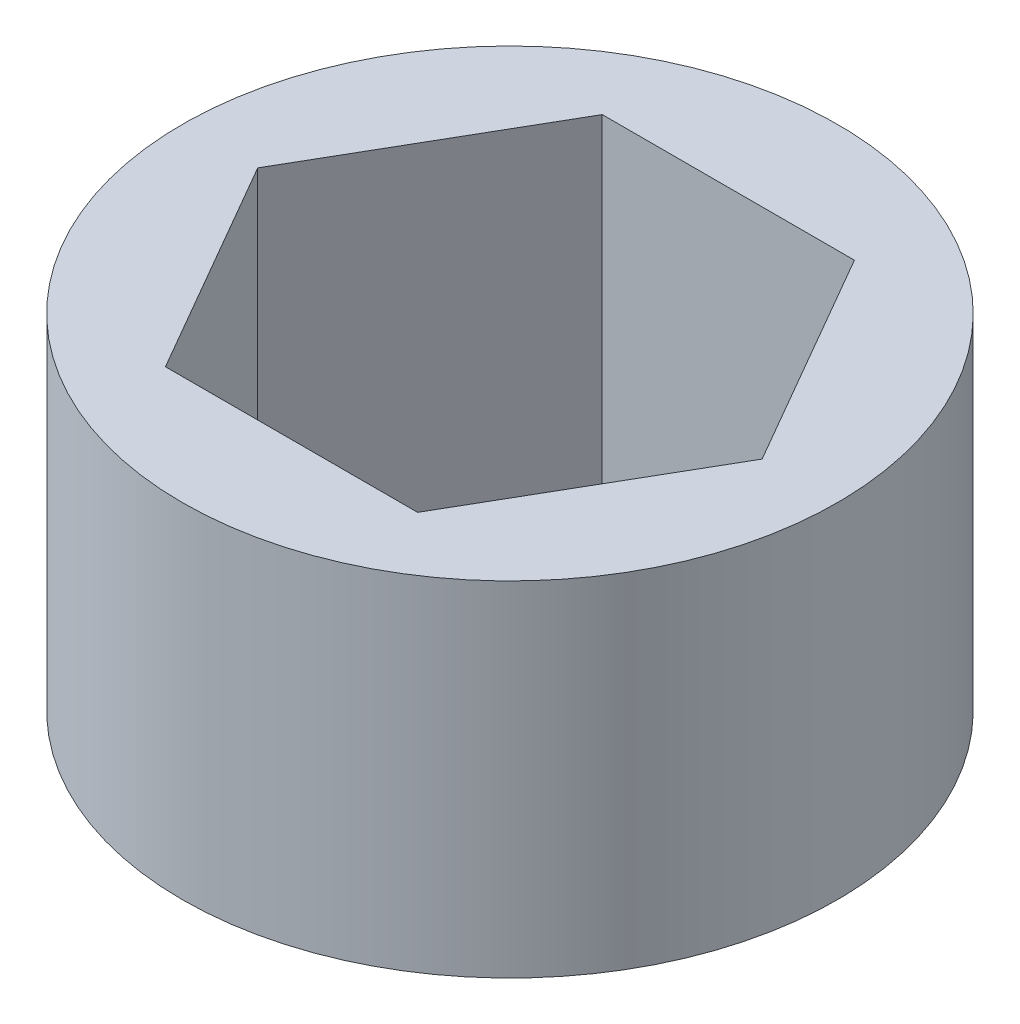
SolidWorks part; units mm, degrees
ref_plane "Alzado" through (0, 0, 0) normal (0, 0, 1) x (1, 0, 0)
ref_plane "Planta" through (0, 0, 0) normal (0, 1, 0) x (1, 0, 0)
ref_plane "Vista lateral" through (0, 0, 0) normal (1, 0, 0) x (0, 0, -1)
sketch "Croquis1" plane through (0, 0, 0) normal (0, 1, 0) x (1, 0, 0)
  line L1 (7.3323, 0) -> (3.6662, 6.35)
  line L2 (3.6662, 6.35) -> (-3.6662, 6.35)
  line L3 (-3.6662, 6.35) -> (-7.3323, 0)
  line L4 (-7.3323, 0) -> (-3.6662, -6.35)
  line L5 (-3.6662, -6.35) -> (3.6662, -6.35)
  line L6 (3.6662, -6.35) -> (7.3323, 0)
  circle A0 centre (0, 0) radius 6.35 construction
  circle A1 centre (0, 0) radius 9.525
  dimension "D2" = 19.05
  dimension "D1" = 12.7
extrude "Saliente-Extruir1" add sketch "Croquis1" along normal blind 10
